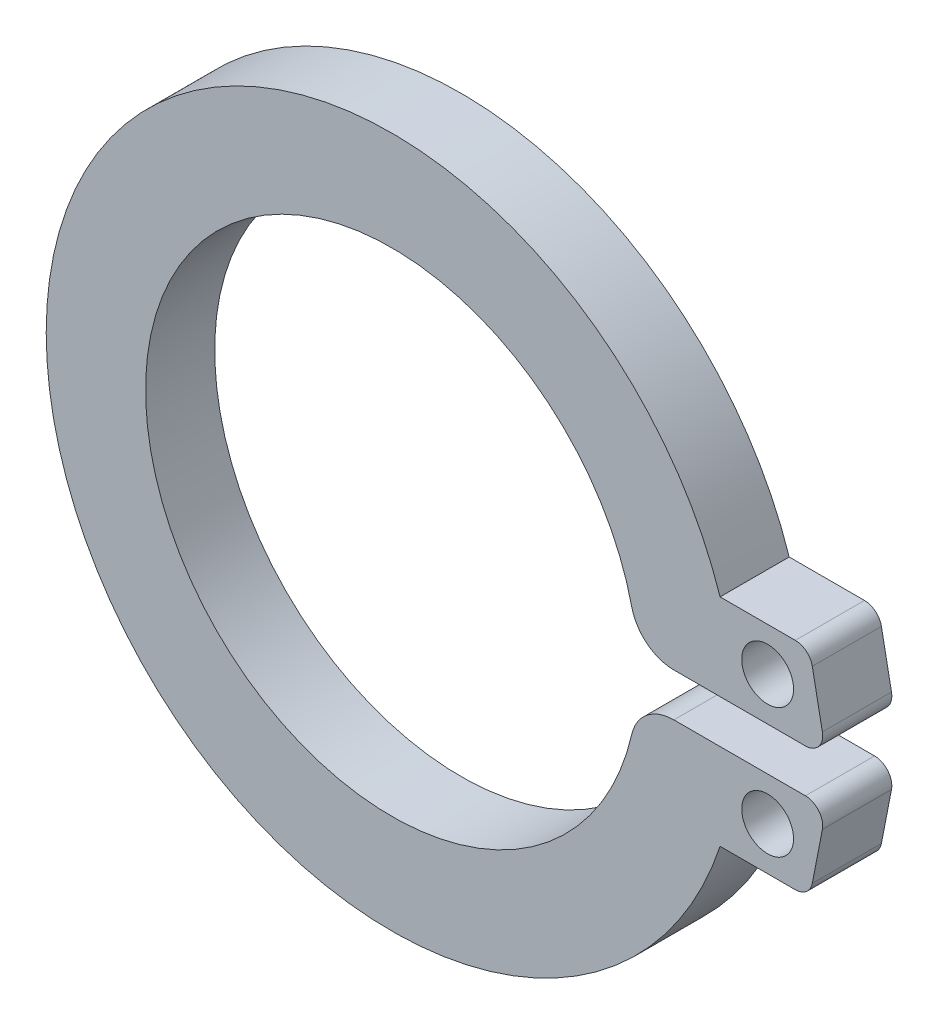
SolidWorks part; units mm, degrees
ref_plane "Front Plane" through (0, 0, 0) normal (1, 0, 0) x (0, 1, 0)
ref_plane "Top Plane" through (0, 0, 0) normal (0, 0, 1) x (0, 1, 0)
ref_plane "Right Plane" through (0, 0, 0) normal (0, 1, 0) x (-1, 0, 0)
sketch "Sketch1" plane through (0, 0, 0) normal (0, 0, 1) x (0, 1, 0)
  line L0 (-5.3357, 0) -> (5.1566, 0) construction
  line L1 (0, -4.2158) -> (0, -5.0869) construction
  line L2 (-0.25, -3.265) -> (-0.25, -4.7874)
  line L4 (0.4882, -4.9837) -> (1.0882, -4.8671)
  line L5 (-1.25, -3.7997) -> (-1.25, -4.6708)
  line L6 (1.25, -2.5608) -> (1.25, -2.5612)
  line L7 (-0.4882, -4.9837) -> (-1.0882, -4.8671)
  line L8 (1.25, -3.7997) -> (1.25, -4.6708)
  line L9 (0.25, -4.7874) -> (0.25, -3.265)
  arc A0 (0.6381, -2.7777) -> (-0.6381, -2.7777) centre (0, 0) ccw
  arc A1 (1.25, -3.7997) -> (-1.25, -3.7997) centre (0, 0) ccw
  circle A2 centre (-0.75, -4.35) radius 0.3
  circle A3 centre (0.75, -4.35) radius 0.3
  arc A4 (0.4882, -4.9837) -> (0.25, -4.7874) centre (0.45, -4.7874) cw
  arc A5 (-0.4882, -4.9837) -> (-0.25, -4.7874) centre (-0.45, -4.7874) ccw
  arc A6 (1.0882, -4.8671) -> (1.25, -4.6708) centre (1.05, -4.6708) ccw
  arc A7 (-1.25, -4.6708) -> (-1.0882, -4.8671) centre (-1.05, -4.6708) ccw
  arc A8 (0.6381, -2.7777) -> (0.25, -3.265) centre (0.75, -3.265) ccw
  arc A9 (-0.25, -3.265) -> (-0.6381, -2.7777) centre (-0.75, -3.265) ccw
  point P18 (0.25, -5.03)
  point P25 (-0.25, -5.03)
  dimension "D1" = 5.7
  dimension "D2" = 8
  dimension "D4" = 0.6
  dimension "D10" = 0.2
  dimension "D11" = 0.5
  dimension "D3" = 0.5
  dimension "D5" = 1.5
  dimension "D6" = 4.35
  dimension "D7" = 79
  dimension "D8" = 1
  dimension "D9" = 0.68
extrude "Boss-Extrude1" add sketch "Sketch1" along normal mid plane 0.8 contours L2 A9 A0 A8 L9 A4 L4 A6 L8 A1 L5 A7 L7 A5 A3 A2
